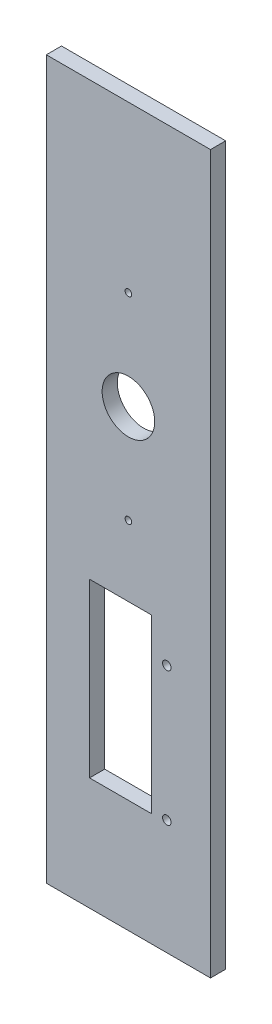
SolidWorks part; units mm, degrees
ref_plane "Front Plane" through (0, 0, 0) normal (0, 0, 1) x (1, 0, 0)
ref_plane "Top Plane" through (0, 0, 0) normal (0, 1, 0) x (1, 0, 0)
ref_plane "Right Plane" through (0, 0, 0) normal (1, 0, 0) x (0, 0, -1)
sketch "Sketch1" plane through (0, 0, 0) normal (0, 0, 1) x (1, 0, 0)
  line B0 (18.0878, -246.64) -> (44.0878, -246.64)
  line B1 (18.0878, -174.64) -> (18.0878, -246.64)
  line B2 (44.0878, -246.64) -> (44.0878, -174.64)
  line B3 (44.0878, -174.64) -> (18.0878, -174.64)
  line B4 (68.7, -293.84) -> (0, -293.84)
  line B5 (68.7, -293.84) -> (68.7, 0)
  line B6 (68.7, 0) -> (0, 0)
  line B7 (0, -293.84) -> (0, 0)
  circle B8 centre (50.4128, -189.74) radius 1.7859
  circle B9 centre (50.4128, -245.74) radius 1.7859
  circle B10 centre (34.35, -145.2) radius 1.3891
  circle B11 centre (34.35, -103.95) radius 11
  circle B12 centre (34.35, -62.7) radius 1.3891
sketch_block_instance "Bottom_OC-1"
sketch_block "Bottom_OC"
extrude "Boss-Extrude1" add sketch "Sketch1" along normal blind 6.35
sketch "Sketch2" plane through (0, 0, 0) normal (0, 1, 0) x (1, 0, 0)
  line L4 (68.7, 0) -> (0, 0)
  line L5 (0, 0) -> (0, -6.35)
  line L6 (0, -6.35) -> (68.7, -6.35)
  line L7 (68.7, -6.35) -> (68.7, 0)
  line L8 (68.7, 0) -> (0, 0)
  line L9 (0, 0) -> (0, -6.35)
  line L10 (0, -6.35) -> (68.7, -6.35)
  line L11 (68.7, -6.35) -> (68.7, 0)
  dimension "D1" = 0
extrude "Boss-Extrude2" add sketch "Sketch2" along normal blind 6.35
